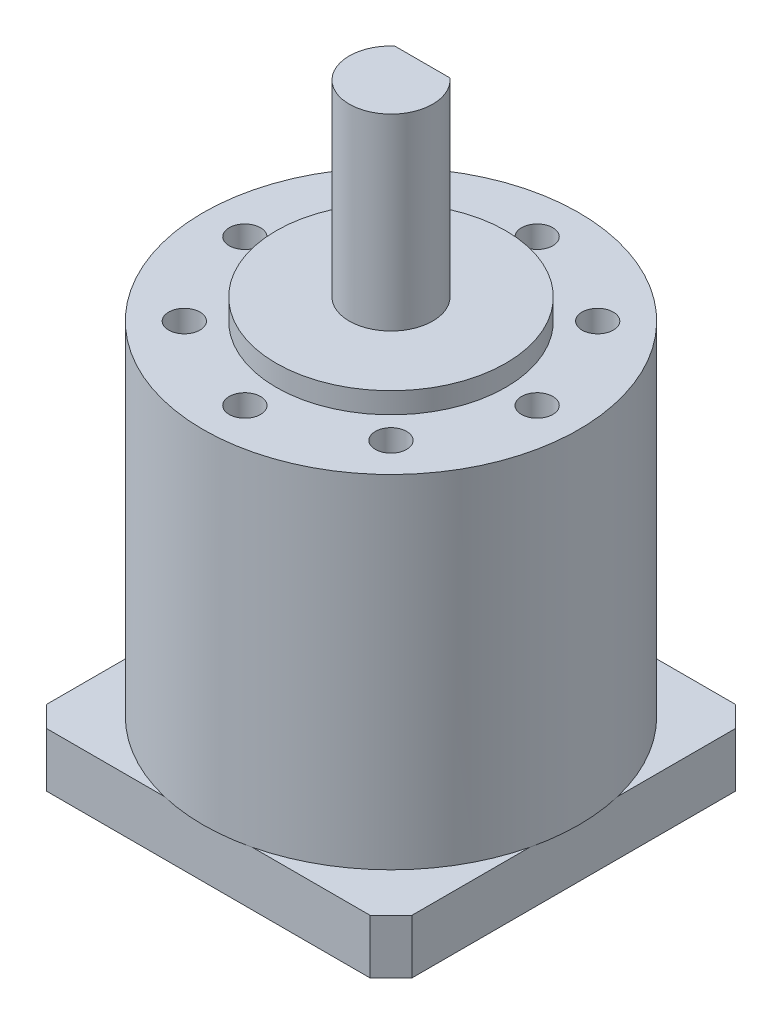
SolidWorks part; units mm, degrees
ref_plane "前视基准面" through (0, 0, 0) normal (0, 0, 1) x (1, 0, 0)
ref_plane "上视基准面" through (0, 0, 0) normal (0, 1, 0) x (1, 0, 0)
ref_plane "右视基准面" through (0, 0, 0) normal (1, 0, 0) x (0, 0, -1)
other "Configuration Table"
sketch "草图1" plane through (0, 0, 0) normal (0, 1, 0) x (1, 0, 0)
  line L1 (-17.5, 17.5) -> (17.5, 17.5)
  line L2 (-17.5, 17.5) -> (-17.5, -17.5)
  line L3 (-17.5, -17.5) -> (17.5, -17.5)
  line L4 (17.5, 17.5) -> (17.5, -17.5)
  line L5 (-17.5, 17.5) -> (17.5, -17.5) construction
  line L6 (-17.5, -17.5) -> (17.5, 17.5) construction
  point P0 (0, 0)
  dimension "D1" = 35
extrude "凸台-拉伸1" add sketch "草图1" along normal blind 5.2
sketch "草图2" plane through (0, 5.2, 0) normal (0, 1, 0) x (1, 0, 0)
  circle A0 centre (0, 0) radius 18
  dimension "D1" = 36
extrude "凸台-拉伸2" add sketch "草图2" along normal blind 32.8
sketch "草图3" plane through (0, 38, 0) normal (0, 1, 0) x (1, 0, 0)
  circle A0 centre (0, 0) radius 11
  dimension "D1" = 22
extrude "凸台-拉伸3" add sketch "草图3" along normal blind 2
sketch "草图4" plane through (0, 40, 0) normal (0, 1, 0) x (1, 0, 0)
  circle A0 centre (0, 0) radius 4
  dimension "D1" = 8
extrude "凸台-拉伸4" add sketch "草图4" along normal blind 18
sketch "草图5" plane through (0, 58, 0) normal (0, 1, 0) x (1, 0, 0)
  line L0 (0, 0) -> (0, 6.8831) construction
  line L2 (5.2734, 10.7663) -> (-5.2734, 10.7663)
  line L3 (5.2734, 10.7663) -> (5.2734, 3)
  line L4 (5.2734, 3) -> (-5.2734, 3)
  line L5 (-5.2734, 10.7663) -> (-5.2734, 3)
  line L6 (5.2734, 10.7663) -> (-5.2734, 3) construction
  line L7 (5.2734, 3) -> (-5.2734, 10.7663) construction
  dimension "D1" = 3
extrude "切除-拉伸1" cut sketch "草图5" against normal blind 15
chamfer "倒角1" distance 2 angle 45 4 edges at (17.5, 2.6, -17.5) (17.5, 2.6, 17.5) (-17.5, 2.6, 17.5) (-17.5, 2.6, -17.5)
sketch "草图6" plane through (0, 38, 0) normal (0, 1, 0) x (1, 0, 0)
  line L0 (0, 0) -> (0, 14) construction
  circle A0 centre (0, 0) radius 14 construction
  circle A1 centre (0, 14) radius 1.5
  circle A2 centre (14, 0) radius 1.5
  circle A3 centre (0, -14) radius 1.5
  circle A4 centre (-14, 0) radius 1.5
  point P14 (0, 0)
  dimension "D1" = 28
  dimension "D2" = 3
  dimension "D3" = 4
extrude "切除-拉伸2" cut sketch "草图6" against normal blind 6
sketch "草图7" plane through (0, 38, 0) normal (0, 1, 0) x (1, 0, 0)
  line L0 (0, 0) -> (-9.8995, 9.8995) construction
  line L1 (0, 0) -> (-14.3341, 0) construction
  circle A0 centre (-9.8995, 9.8995) radius 1.5
  circle A2 centre (9.8995, 9.8995) radius 1.5
  circle A3 centre (9.8995, -9.8995) radius 1.5
  circle A4 centre (-9.8995, -9.8995) radius 1.5
  point P14 (0, 0)
  dimension "D3" = 3
  dimension "D1" = 45
  dimension "D2" = 14
  dimension "D4" = 4
extrude "切除-拉伸3" cut sketch "草图7" against normal blind 6
